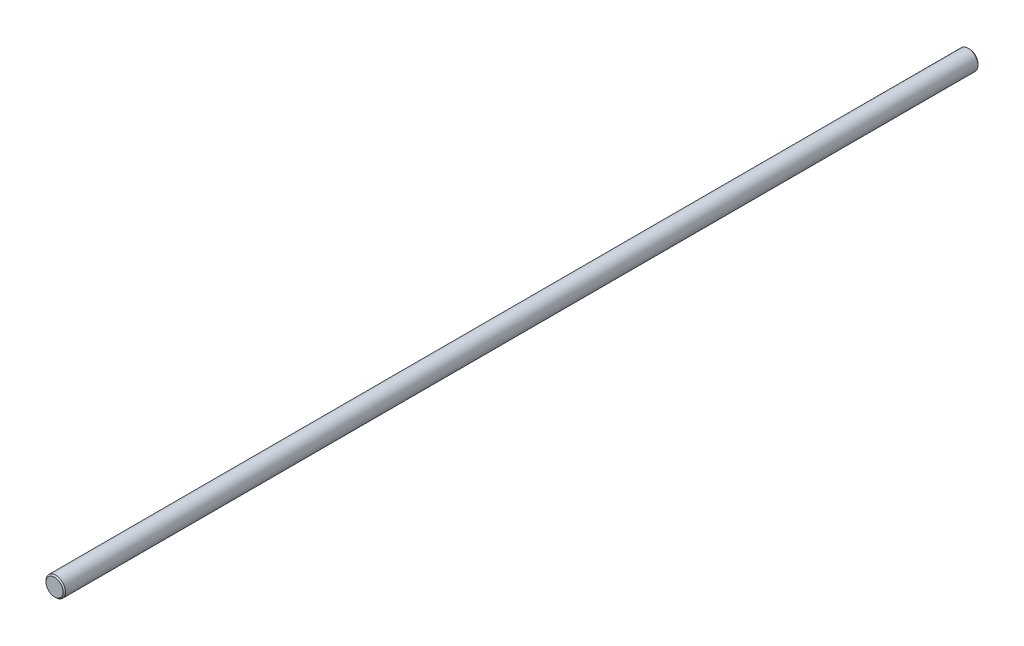
SolidWorks part; units mm, degrees
material "1023 Arkusz stali węglowej (SS)"
ref_plane "Płaszczyzna przednia" through (0, 0, 0) normal (0, 0, 1) x (1, 0, 0)
ref_plane "Płaszczyzna górna" through (0, 0, 0) normal (0, 1, 0) x (1, 0, 0)
ref_plane "Płaszczyzna prawa" through (0, 0, 0) normal (1, 0, 0) x (0, 0, -1)
sketch "Szkic1" plane through (0, 0, 0) normal (0, 0, 1) x (1, 0, 0)
  circle A0 centre (0, 0) radius 4
  dimension "D1" = 8
extrude "Dodanie-wyciągnięcie1" add sketch "Szkic1" along normal blind 375
chamfer "Sfazowanie1" distance 0.5 angle 45 2 edges at (4, 0, 375) (4, 0, 0)
